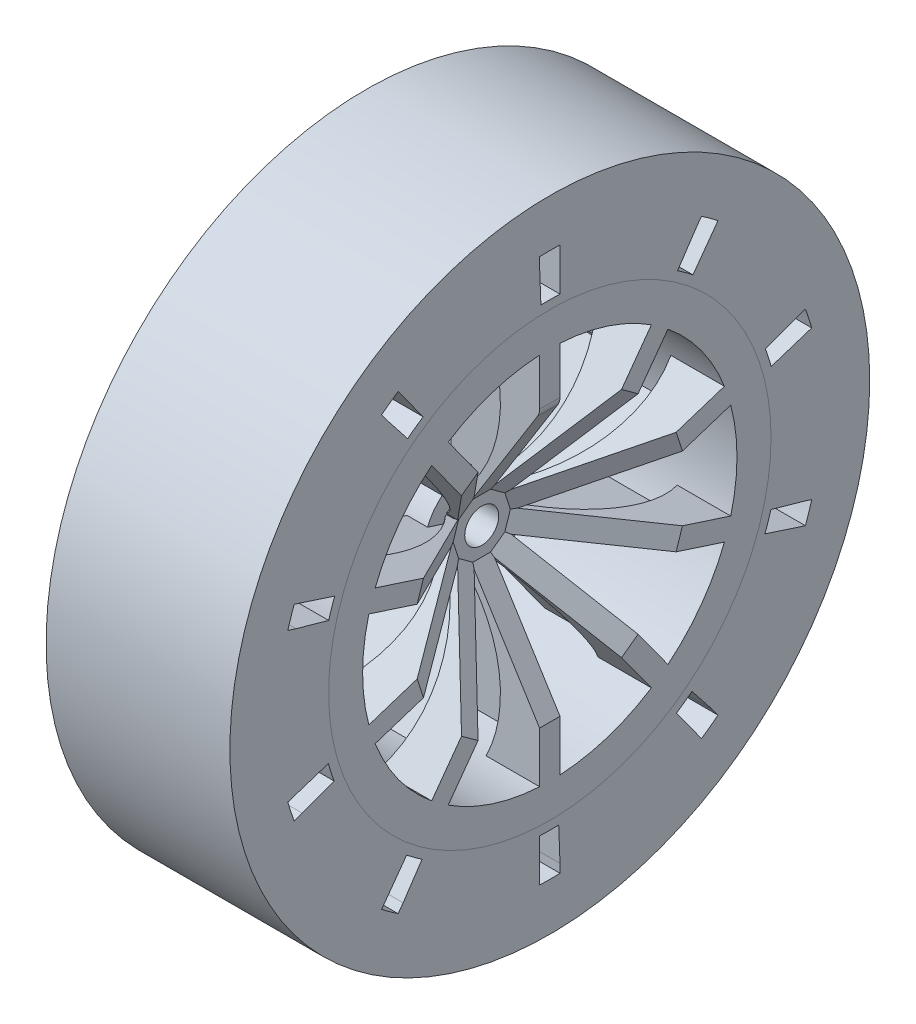
SolidWorks part; units mm, degrees
ref_plane "前视基准面" through (0, 0, 0) normal (0, 0, 1) x (1, 0, 0)
ref_plane "上视基准面" through (0, 0, 0) normal (0, 1, 0) x (1, 0, 0)
ref_plane "右视基准面" through (0, 0, 0) normal (1, 0, 0) x (0, 0, -1)
sketch "草图1" plane through (0, 0, 0) normal (1, 0, 0) x (0, 0, -1)
  circle A0 centre (0, 0) radius 32.5
  circle A1 centre (0, 0) radius 27.5
  dimension "D1" = 65
  dimension "D2" = 55
extrude "凸台-拉伸1" add sketch "草图1" along normal blind 27
sketch "草图2" plane through (0, 0, 0) normal (0, 0, 1) x (1, 0, 0)
  line L0 (27, 27.5) -> (27, 20)
  line L1 (27, -32.5) -> (27, 32.5) construction
  line L2 (27, -27.5) -> (27, 27.5) construction
  line L3 (27, 20) -> (17, 4)
  line L4 (27, 27.5) -> (19.1175, 27.5)
  line L5 (17, 4) -> (15, 4)
  arc A0 (15, 4) -> (19.1175, 27.5) centre (1.2466, 18.5205) ccw
  dimension "D5" = 20
  dimension "D2" = 10
  dimension "D3" = 4
  dimension "D6" = 2
extrude "凸台-拉伸2" add sketch "草图2" along normal mid plane 3
sketch "草图5" plane through (0, 0, 0) normal (0, 0, 1) x (1, 0, 0)
  line L0 (13, 23.2376) -> (13, 4)
  line L1 (13, 4) -> (15.7578, 4)
  line L2 (15.7578, 4) -> (19.73, 9.2407)
  line L3 (19.73, 9.2407) -> (23.1137, 17.087)
  line L4 (23.1137, 17.087) -> (23.1137, 23.2376)
  line L5 (23.1137, 23.2376) -> (13, 23.2376)
  dimension "D1" = 4
  dimension "D2" = 4
extrude "凸台-拉伸5" add sketch "草图5" along normal mid plane 1
fillet "圆角2" radius 2 1 edges at (27, 20, 0)
pattern_circular "阵列(圆周)1" count 10 over 360 about axis through (0, 0, 0) along (1, 0, 0) of "凸台-拉伸2", "凸台-拉伸5"
sketch "草图3" plane through (27, 0, 0) normal (1, 0, 0) x (0, 0, -1)
  circle A0 centre (0, 0) radius 5
  dimension "D1" = 10
extrude "凸台-拉伸3" add sketch "草图3" against normal blind 10 from vertex at -10
sketch "草图4" plane through (27, 0, 0) normal (1, 0, 0) x (0, 0, -1)
  circle A0 centre (0, 0) radius 32.5
  circle A1 centre (0, 0) radius 47
  circle M41 centre (0, 0) radius 32.5
  dimension "D1" = 94
  dimension "D2" = 65
extrude "凸台-拉伸4" add sketch "草图4" against normal blind 27 separate body contours A1 M41
sketch "草图6" plane through (7, 0, 0) normal (-1, 0, 0) x (0, 0, 1)
  circle A0 centre (0, 0) radius 7.5
  dimension "D1" = 15
extrude "凸台-拉伸6" add sketch "草图6" against normal blind 9
sketch "草图7" plane through (7, 0, 0) normal (-1, 0, 0) x (0, 0, 1)
  line L1 (6.9282, 0) -> (3.4641, 6)
  line L2 (3.4641, 6) -> (-3.4641, 6)
  line L3 (-3.4641, 6) -> (-6.9282, 0)
  line L4 (-6.9282, 0) -> (-3.4641, -6)
  line L5 (-3.4641, -6) -> (3.4641, -6)
  line L6 (3.4641, -6) -> (6.9282, 0)
  circle A0 centre (0, 0) radius 6 construction
  dimension "D1" = 12
extrude "切除-拉伸2" cut sketch "草图7" against normal blind 6
sketch "草图8" plane through (13, 0, 0) normal (-1, 0, 0) x (0, 0, 1)
  circle A0 centre (0, 0) radius 2.5
  dimension "D1" = 5
extrude "切除-拉伸3" cut sketch "草图8" against normal blind 6
sketch "草图9" plane through (27, 0, 0) normal (1, 0, 0) x (0, 0, -1)
  line L0 (-1.5, 38.721) -> (-1.5, 39.9719)
  line L1 (1.5, 33.7155) -> (1.5, 39.9719)
  line L2 (18.6039, 28.1581) -> (22.2813, 33.2196)
  line L3 (10.5422, 17.062) -> (14.9265, 23.0965) construction
  line L4 (-1.5, 38.721) -> (-1.3064, 33.7235)
  circle A0 centre (0, 0) radius 40
  circle A1 centre (0, 0) radius 38.75
  arc A4 (18.6039, 28.1581) -> (1.5, 33.7155) centre (0, 0) ccw
  arc A5 (1.5, 33.7155) -> (-1.3064, 33.7235) centre (0, 0) ccw
  dimension "D1" = 77.5
  dimension "D2" = 80
sketch "草图12" plane through (0, 0, 0) normal (0, 0, 1) x (1, 0, 0)
  line L0 (0, 0) -> (50000, 0) construction
extrude "切除-拉伸4" cut sketch "草图9" against normal blind 10 contours A5 L1 A1 L4 | A1 L1 A0 L0
pattern_circular "阵列(圆周)2" count 10 every 36 about axis through (0, 0, 0) along (1, 0, 0) of "切除-拉伸4"
ref_plane "基准面1" through (13.5, 0, 0) normal (1, 0, 0) x (0, 0, -1)
mirror "镜向1" about plane through (13.5, 0, 0) normal (1, 0, 0) of "阵列(圆周)2", "切除-拉伸4"
